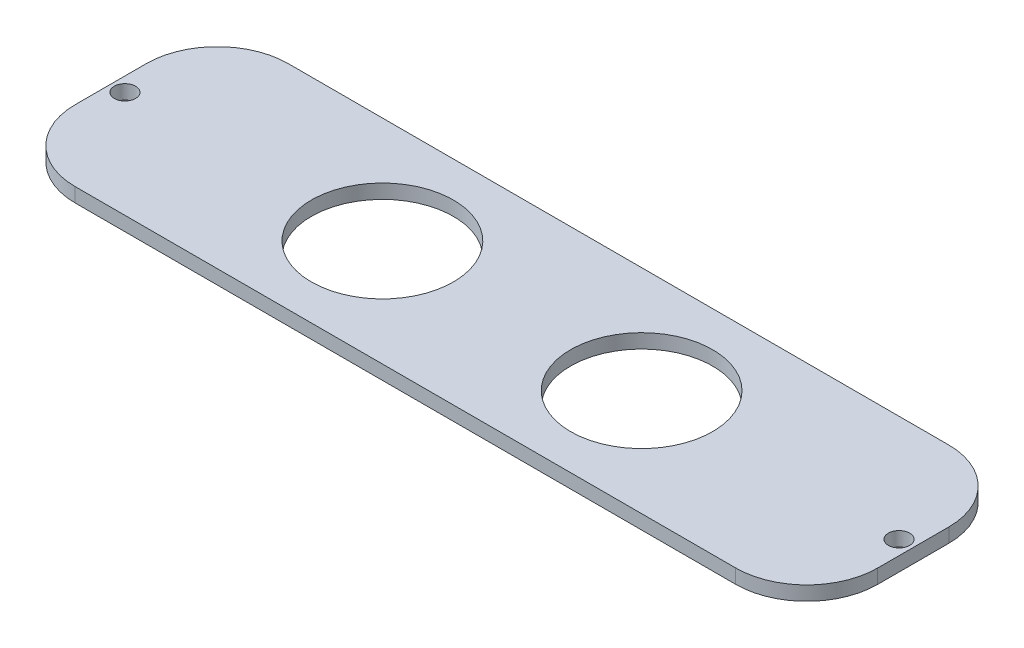
SolidWorks part; units mm, degrees
material "Hexcel AS4C (3000 丝)"
ref_plane "前视基准面" through (0, 0, 0) normal (0, 0, 1) x (1, 0, 0)
ref_plane "上视基准面" through (0, 0, 0) normal (0, 1, 0) x (1, 0, 0)
ref_plane "右视基准面" through (0, 0, 0) normal (1, 0, 0) x (0, 0, -1)
other "Configuration Table"
sketch "草图1" plane through (0, 0, 0) normal (0, 1, 0) x (1, 0, 0)
  line L0 (-56.5, 0) -> (-54.5, 0) construction
  line L1 (-46.5, -15) -> (46.5, -15)
  line L2 (-56.5, -5) -> (-56.5, 5)
  line L3 (-46.5, 15) -> (46.5, 15)
  line L4 (56.5, -5) -> (56.5, 5)
  line L5 (-56.5, -15) -> (56.5, 15) construction
  line L6 (-56.5, 15) -> (56.5, -15) construction
  line L7 (-18.25, 0) -> (18.25, 0) construction
  line L8 (56.5, 0) -> (54.5, 0) construction
  circle A0 centre (18.25, 0) radius 10
  circle A1 centre (-18.25, 0) radius 10
  circle A2 centre (-54.5, 0) radius 1.5
  circle A3 centre (54.5, 0) radius 1.5
  arc A4 (-46.5, -15) -> (-56.5, -5) centre (-46.5, -5) cw
  arc A5 (46.5, -15) -> (56.5, -5) centre (46.5, -5) ccw
  arc A6 (46.5, 15) -> (56.5, 5) centre (46.5, 5) cw
  arc A7 (-56.5, 5) -> (-46.5, 15) centre (-46.5, 5) cw
  point P0 (0, 0)
  dimension "D3" = 20
  dimension "D6" = 3
  dimension "D7" = 10
  dimension "D1" = 30
  dimension "D2" = 36.5
  dimension "D4" = 113
  dimension "D5" = 2
extrude "凸台-拉伸1" add sketch "草图1" along normal blind 2
